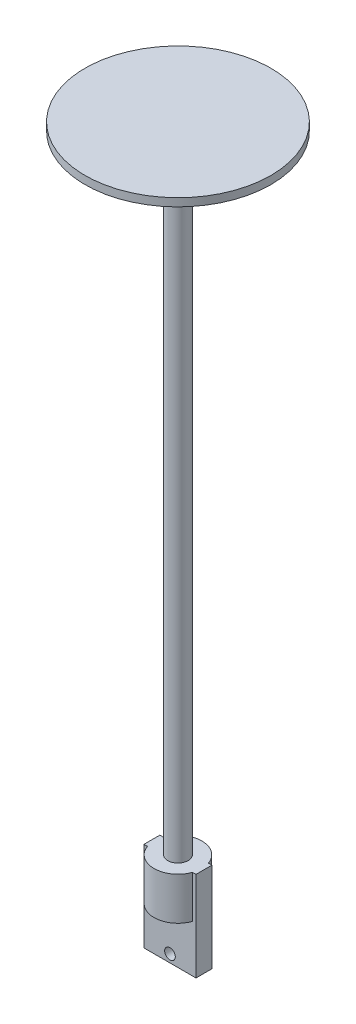
SolidWorks part; units mm, degrees
ref_plane "Front Plane" through (0, 0, 0) normal (0, 0, 1) x (1, 0, 0)
ref_plane "Top Plane" through (0, 0, 0) normal (0, 1, 0) x (1, 0, 0)
ref_plane "Right Plane" through (0, 0, 0) normal (1, 0, 0) x (0, 0, -1)
sketch "Sketch1" plane through (0, 0, 0) normal (0, 0, 1) x (1, 0, 0)
  line L5 (4.9, -4.45) -> (-4.9, -4.45)
  line L6 (4.9, -4.45) -> (4.9, 4.45)
  line L7 (4.9, 4.45) -> (-4.9, 4.45)
  line L8 (-4.9, -4.45) -> (-4.9, 4.45)
  line L9 (4.9, -4.45) -> (-4.9, 4.45) construction
  line L10 (4.9, 4.45) -> (-4.9, -4.45) construction
  circle A1 centre (0, -2.95) radius 1
  point P0 (0, 0)
  point P1 (0, 0)
  dimension "D1" = 9.8
  dimension "D2" = 2
  dimension "D3" = 1.5
  dimension "D4" = 7.4
extrude "Boss-Extrude2" add sketch "Sketch1" along normal blind 3
sketch "Sketch3" plane through (0, 4.45, 0) normal (0, 1, 0) x (1, 0, 0)
  line L0 (4.9, -3) -> (4.9, 0) construction
  line L1 (4.9, -3) -> (-4.9, -3) construction
  line L2 (4.9, 0) -> (-4.9, 0) construction
  line L3 (-4.9, -3) -> (-4.9, 0) construction
  line L4 (4.9, -3) -> (4.9, 0)
  line L5 (4.9, -3) -> (4.2426, -3)
  line L6 (4.9, 0) -> (4.2426, 0)
  line L7 (-4.9, -3) -> (-4.9, 0)
  line L8 (-4.2426, 0) -> (-4.9, 0)
  line L9 (-4.2426, -3) -> (-4.9, -3)
  arc A0 (-4.2426, -3) -> (4.2426, -3) centre (0, -1.5) ccw
  arc A1 (4.2426, 0) -> (-4.2426, 0) centre (0, -1.5) ccw
  point P0 (0, -1.5)
  dimension "D1" = 9
extrude "Boss-Extrude4" add sketch "Sketch3" along normal blind 10
sketch "Sketch4" plane through (0, 14.45, 0) normal (0, 1, 0) x (1, 0, 0)
  circle A0 centre (0, -1.5) radius 1.925
  dimension "D1" = 3.85
extrude "Boss-Extrude5" add sketch "Sketch4" along normal blind 116
ref_plane "Plane7" through (0, 0, 1.5) normal (0, 0, 1) x (1, 0, 0)
sketch "Sketch7" plane through (0, 0, 1.5) normal (0, 0, 1) x (1, 0, 0)
  line L0 (1.925, 130.45) -> (-1.925, 130.45) construction
  line L1 (1.925, 130.45) -> (0, 130.45)
  line L2 (1.925, 130.45) -> (1.925, 122.65)
  line L3 (1.925, 14.45) -> (1.925, 130.45) construction
  line L4 (3.2309, 123.05) -> (6.926, 129.45)
  line L5 (0, 130.45) -> (0, 134.2296) construction
  line L6 (1.925, 122.65) -> (2.5381, 122.65)
  line L7 (17.5, 130.45) -> (8.658, 130.45)
  line L8 (1.925, 130.45) -> (-1.925, 130.45)
  line L9 (0, 131.95) -> (17.5, 131.95)
  line L10 (17.5, 131.95) -> (17.5, 130.45)
  line L11 (0, 131.95) -> (0, 130.45)
  arc A0 (3.2309, 123.05) -> (2.5381, 122.65) centre (2.5381, 123.45) cw
  arc A1 (6.926, 129.45) -> (8.658, 130.45) centre (8.658, 128.45) cw
  point P12 (3, 122.65)
  point P16 (0, 130.45)
  point P21 (7.5033, 130.45)
  dimension "D4" = 0.8
  dimension "D5" = 15.0067
  dimension "D7" = 2
  dimension "D1" = 7.8
  dimension "D2" = 3
  dimension "D3" = 30
  dimension "D6" = 35
  dimension "D8" = 1.5
revolve "Revolve1" add sketch "Sketch7" angle 360 about L5
sketch "Sketch8" plane through (0, 14.45, 0) normal (0, 1, 0) x (1, 0, 0)
  line L6 (-4.2426, 0) -> (-4.9, 0)
  line L7 (-4.9, 0) -> (-4.9, -3)
  line L8 (-4.9, -3) -> (-4.2426, -3)
  line L9 (4.2426, -3) -> (4.9, -3)
  line L10 (4.9, -3) -> (4.9, 0)
  line L11 (4.9, 0) -> (4.2426, 0)
  line L12 (-4.2426, 0) -> (-4.9, 0)
  line L13 (-4.9, 0) -> (-4.9, -3)
  line L14 (-4.9, -3) -> (-4.2426, -3)
  line L15 (4.2426, -3) -> (4.9, -3)
  line L16 (4.9, -3) -> (4.9, 0)
  line L17 (4.9, 0) -> (4.2426, 0)
  arc A2 (4.2426, 0) -> (-4.2426, 0) centre (0, -1.5) ccw
  arc A3 (-4.2426, -3) -> (4.2426, -3) centre (0, -1.5) ccw
  arc A4 (4.2426, 0) -> (-4.2426, 0) centre (0, -1.5) ccw
  arc A5 (-4.2426, -3) -> (4.2426, -3) centre (0, -1.5) ccw
  dimension "D1" = 0
extrude "Cut-Extrude1" cut sketch "Sketch8" against normal blind 2
sketch "Sketch9" plane through (0, 14.45, 0) normal (0, -1, 0) x (1, 0, 0)
  circle A1 centre (0, 1.5) radius 1.925
  circle A2 centre (0, 1.5) radius 1.925
  dimension "D1" = 0
extrude "Boss-Extrude6" add sketch "Sketch9" along normal up to body
